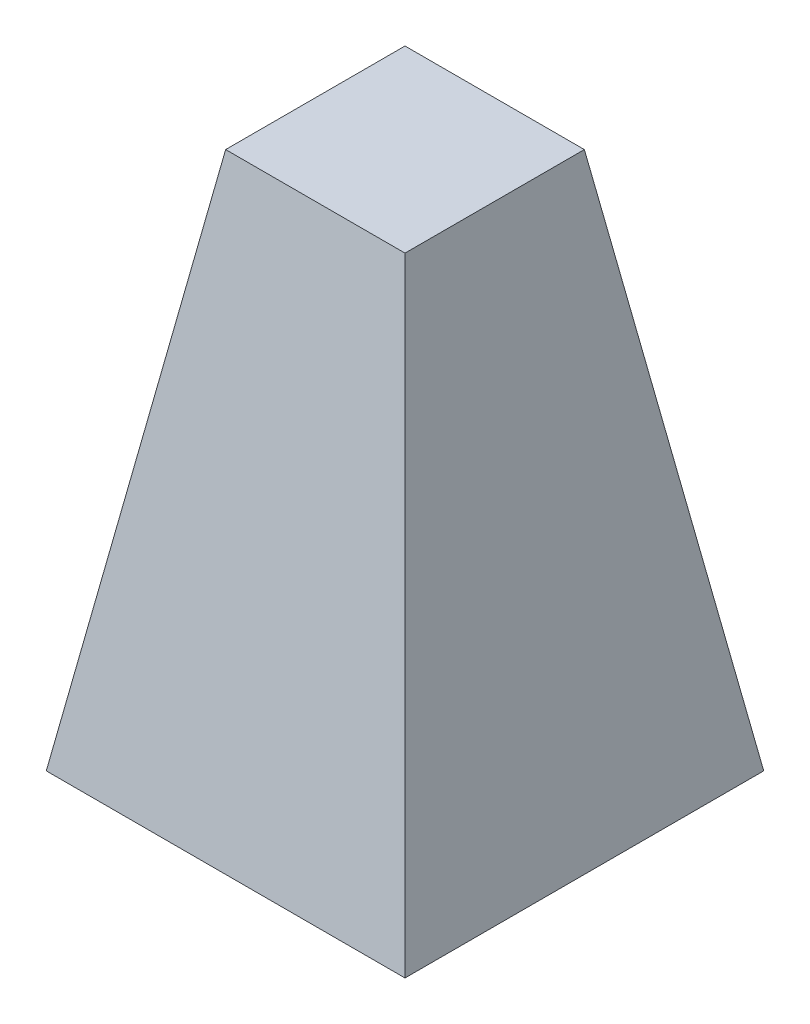
SolidWorks part; units mm, degrees
ref_plane "前视基准面" through (0, 0, 0) normal (0, 0, 1) x (1, 0, 0)
ref_plane "上视基准面" through (0, 0, 0) normal (0, 1, 0) x (1, 0, 0)
ref_plane "右视基准面" through (0, 0, 0) normal (1, 0, 0) x (0, 0, -1)
sketch "草图1" plane through (0, 0, 0) normal (0, 1, 0) x (1, 0, 0)
  line L1 (0, 0) -> (50, 0)
  line L2 (0, 0) -> (0, 50)
  line L3 (0, 50) -> (50, 50)
  line L4 (50, 0) -> (50, 50)
ref_plane "基准面2" through (0, 0, -25) normal (0, 0, 1) x (1, 0, 0)
sketch "草图2" plane through (0, 0, -25) normal (0, 0, 1) x (1, 0, 0)
  line L0 (25, 0) -> (25, 75)
  line L1 (0, 0) -> (50, 0) construction
ref_plane "基准面3" through (0, 75, 0) normal (0, 1, 0) x (1, 0, 0)
sketch "草图3" plane through (0, 75, 0) normal (0, 1, 0) x (1, 0, 0)
  line L0 (-27.5, 25) -> (27.5, 25) construction
  line L1 (37.5, 37.5) -> (12.5, 37.5)
  line L2 (12.5, 37.5) -> (12.5, 12.5)
  line L3 (12.5, 12.5) -> (37.5, 12.5)
  line L4 (37.5, 12.5) -> (37.5, 37.5)
  circle A0 centre (25, 25) radius 12.5 construction
loft "放样1" add profiles "草图1", "草图3"
